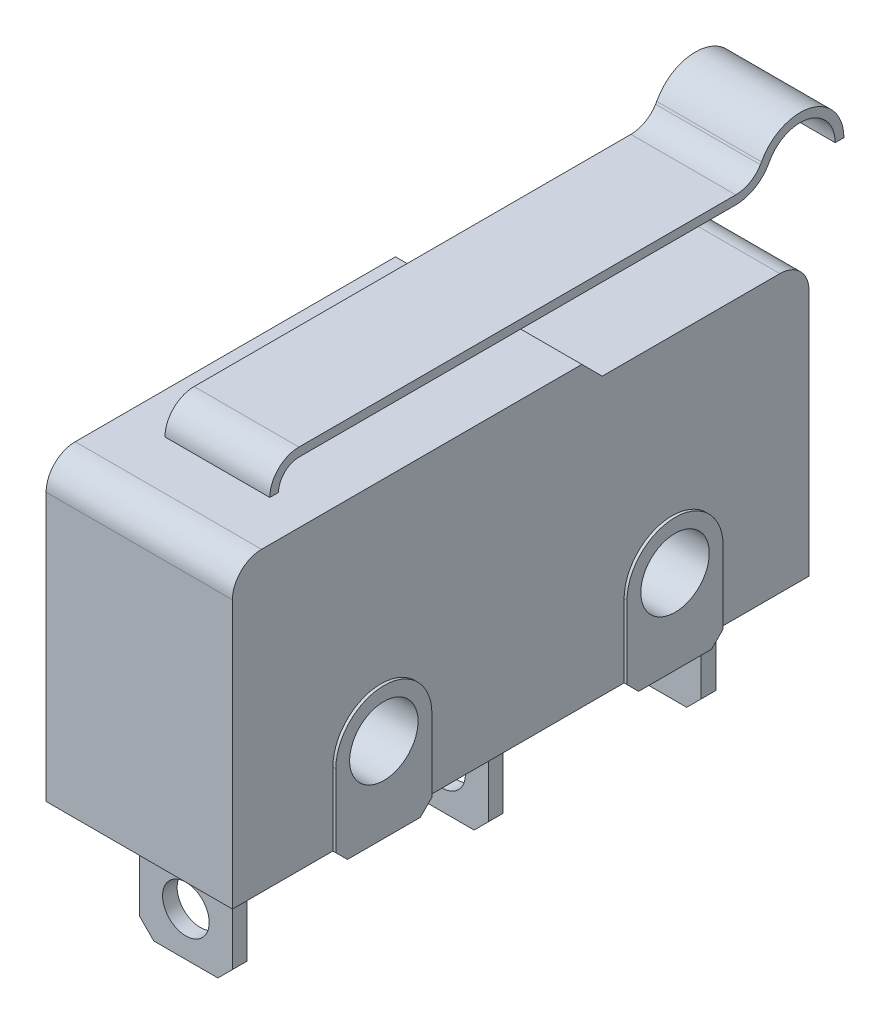
SolidWorks part; units mm, degrees
ref_plane "正面" through (0, 0, 0) normal (0, 0, 1) x (1, 0, 0)
ref_plane "平面" through (0, 0, 0) normal (0, 1, 0) x (1, 0, 0)
ref_plane "右側面" through (0, 0, 0) normal (1, 0, 0) x (0, 0, -1)
sketch "ｽｹｯﾁ1" plane through (0, 0, 0) normal (1, 0, 0) x (0, 0, -1)
  line L0 (12, 10.2) -> (12.7, 9.5)
  line L1 (0, 0) -> (19.8, 0)
  line L2 (0, 0) -> (0, 9.2)
  line L3 (12.7, 9.5) -> (18.8, 9.5)
  line L4 (19.8, 0) -> (19.8, 8.5)
  line L7 (1, 10.2) -> (12, 10.2)
  arc A0 (18.8, 9.5) -> (19.8, 8.5) centre (18.8, 8.5) cw
  arc A1 (0, 9.2) -> (1, 10.2) centre (1, 9.2) cw
  point P7 (19.8, 9.5)
  dimension "D3" = 1
  dimension "D5" = 1
  dimension "D1" = 19.8
  dimension "D2" = 9.5
  dimension "D4" = 10.2
  dimension "D6" = 12
  dimension "D7" = 135
extrude "ﾎﾞｽ - 押し出し1" add sketch "ｽｹｯﾁ1" along normal mid plane 6.4
sketch "ｽｹｯﾁ3" plane through (0, 0, 0) normal (1, 0, 0) x (0, 0, -1)
  line L0 (0, 0) -> (19.8, 0) construction
  line L1 (1.6, 0) -> (2.1, 0)
  line L2 (1.6, 0) -> (1.6, -3.9)
  line L3 (1.6, -3.9) -> (2.1, -3.9)
  line L4 (2.1, 0) -> (2.1, -3.9)
  line L5 (0, 9.2) -> (0, 0) construction
  line L6 (10.4, 0) -> (10.9, 0)
  line L7 (10.4, 0) -> (10.4, -3.9)
  line L8 (10.4, -3.9) -> (10.9, -3.9)
  line L9 (10.9, 0) -> (10.9, -3.9)
  line L10 (17.7, 0) -> (18.2, 0)
  line L11 (17.7, 0) -> (17.7, -3.9)
  line L12 (17.7, -3.9) -> (18.2, -3.9)
  line L13 (18.2, 0) -> (18.2, -3.9)
  dimension "D1" = 0.5
  dimension "D2" = 3.9
  dimension "D3" = 1.6
  dimension "D4" = 8.8
  dimension "D5" = 7.3
extrude "ﾎﾞｽ - 押し出し3" add sketch "ｽｹｯﾁ3" along normal mid plane 3.2
chamfer "面取り1" distance 0.5 angle 45 6 edges at (-1.6, -3.9, -17.95) (-1.6, -3.9, -10.65) (-1.6, -3.9, -1.85) (1.6, -3.9, -17.95) (1.6, -3.9, -10.65) (1.6, -3.9, -1.85)
sketch "ｽｹｯﾁ4" plane through (0, 0, -18.2) normal (0, 0, -1) x (-1, 0, 0)
  line L0 (0, 0) -> (0, -3.9) construction
  line L1 (-1.1, -3.9) -> (1.1, -3.9) construction
  circle A0 centre (0, -2.4) radius 0.8
  dimension "D1" = 1.6
  dimension "D2" = 1.5
extrude "ｶｯﾄ - 押し出し1" cut sketch "ｽｹｯﾁ4" against normal through all
sketch "ｽｹｯﾁ5" plane through (3.2, 0, 0) normal (1, 0, 0) x (0, 0, -1)
  line L0 (3.45, 2.5) -> (3.45, 0)
  line L1 (0, 0) -> (19.8, 0) construction
  line L2 (3.45, 0) -> (3.85, -0.4)
  line L3 (3.85, -0.4) -> (6.35, -0.4)
  line L4 (6.35, -0.4) -> (6.75, 0)
  line L5 (6.75, 0) -> (6.75, 2.5)
  line L6 (0, 9.2) -> (0, 0) construction
  arc A0 (6.75, 2.5) -> (3.45, 2.5) centre (5.1, 2.5) ccw
  dimension "D1" = 5.1
  dimension "D2" = 2.9
  dimension "D3" = 225
  dimension "D4" = 135
  dimension "D5" = 2.5
  dimension "D6" = 0.4
extrude "ﾎﾞｽ - 押し出し4" add sketch "ｽｹｯﾁ5" along normal blind 0.1
pattern_linear "直線ﾊﾟﾀｰﾝ1" count 2 spacing 10 along (0, 0, -1) of "ﾎﾞｽ - 押し出し4"
mirror "ﾐﾗｰ1" about plane through (0, 0, 0) normal (1, 0, 0) of "直線ﾊﾟﾀｰﾝ1", "ﾎﾞｽ - 押し出し4"
sketch "ｽｹｯﾁ6" plane through (3.3, 0, 0) normal (1, 0, 0) x (0, 0, -1)
  circle A0 centre (5.1, 2.5) radius 1.175
  circle A1 centre (15.1, 2.5) radius 1.175
  dimension "D1" = 2.35
extrude "ｶｯﾄ - 押し出し2" cut sketch "ｽｹｯﾁ6" against normal through all
sketch "ｽｹｯﾁ2" plane through (0, 0, 0) normal (1, 0, 0) x (0, 0, -1)
  line L0 (12, 10.2) -> (1, 10.2) construction
  line L1 (3.6837, 11.2) -> (18.6837, 11.2)
  line L3 (3.6837, 10.9) -> (18.6837, 10.9)
  line L5 (2.6837, 10.2) -> (2.9837, 10.2)
  line L6 (22.1, 11.0432) -> (22.4, 11.0432)
  line L7 (0, 9.2) -> (0, 0) construction
  line L8 (19.5326, 11.6714) -> (19.5702, 11.7373) construction
  line L9 (19.7905, 11.518) -> (19.8337, 11.5937) construction
  line L10 (19.5702, 11.7373) -> (19.5326, 11.6714)
  line L11 (19.8337, 11.5937) -> (19.7905, 11.518)
  arc A0 (2.6837, 10.2) -> (3.6837, 11.2) centre (3.6837, 10.2) cw
  arc A1 (19.5702, 11.7373) -> (22.4, 11.0432) centre (20.9, 11.0432) cw
  arc A2 (18.6837, 11.2) -> (19.5326, 11.6714) centre (18.6837, 12.2) ccw
  arc A3 (2.9837, 10.2) -> (3.6837, 10.9) centre (3.6837, 10.2) cw
  arc A4 (18.6837, 10.9) -> (19.7905, 11.518) centre (18.6837, 12.2) ccw
  arc A5 (19.8337, 11.5937) -> (22.1, 11.0432) centre (20.9, 11.0432) cw
  arc A6 (19.5702, 11.7373) -> (22.4, 11.0432) centre (20.9, 11.0432) cw construction
  circle A7 centre (15.1, 2.5) radius 1.175 construction
  point P27 (21.2573, 12.5)
  dimension "D1" = 1
  dimension "D5" = 1
  dimension "D6" = 1.5
  dimension "D3" = 20.9
  dimension "D4" = 10
  dimension "D7" = 15
  dimension "D2" = 0.3
extrude "ﾎﾞｽ - 押し出し2" add sketch "ｽｹｯﾁ2" along normal mid plane 3.6
